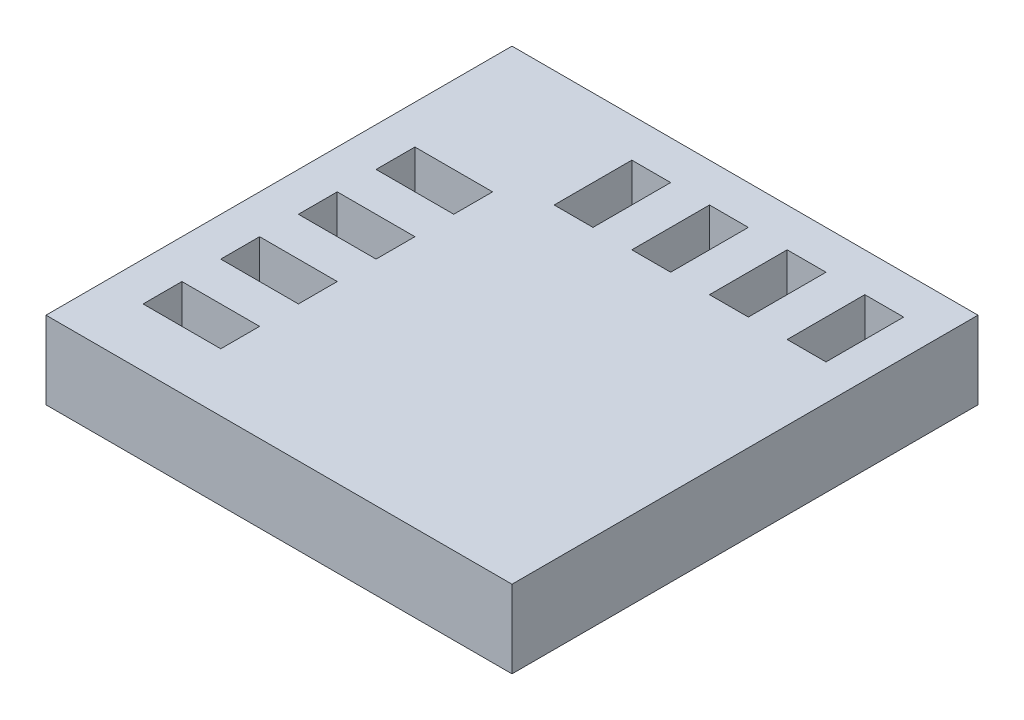
SolidWorks part; units mm, degrees
ref_plane "Front Plane" through (0, 0, 0) normal (0, 0, 1) x (1, 0, 0)
ref_plane "Top Plane" through (0, 0, 0) normal (0, 1, 0) x (1, 0, 0)
ref_plane "Right Plane" through (0, 0, 0) normal (1, 0, 0) x (0, 0, -1)
sketch "Sketch1" plane through (0, 0, 0) normal (0, 1, 0) x (1, 0, 0)
  line L0 (-31.75, -3.175) -> (-19.05, -3.175)
  line L1 (-38.1, -38.1) -> (38.1, -38.1)
  line L2 (-38.1, -38.1) -> (-38.1, 38.1)
  line L3 (-38.1, 38.1) -> (38.1, 38.1)
  line L4 (38.1, -38.1) -> (38.1, 38.1)
  line L5 (-38.1, -38.1) -> (38.1, 38.1) construction
  line L6 (-38.1, 38.1) -> (38.1, -38.1) construction
  line L7 (-31.75, 15.875) -> (-19.05, 15.875)
  line L8 (-31.75, 15.875) -> (-31.75, 9.525)
  line L9 (-31.75, 9.525) -> (-19.05, 9.525)
  line L10 (-19.05, 15.875) -> (-19.05, 9.525)
  line L11 (-31.75, 15.875) -> (-19.05, 9.525) construction
  line L12 (-31.75, 9.525) -> (-19.05, 15.875) construction
  line L13 (-19.05, 3.175) -> (-19.05, -3.175)
  line L14 (-31.75, 3.175) -> (-19.05, 3.175)
  line L15 (-31.75, 3.175) -> (-31.75, -3.175)
  line L16 (-31.75, -15.875) -> (-19.05, -15.875)
  line L17 (-19.05, -9.525) -> (-19.05, -15.875)
  line L18 (-31.75, -9.525) -> (-19.05, -9.525)
  line L19 (-31.75, -9.525) -> (-31.75, -15.875)
  line L20 (-31.75, -28.575) -> (-19.05, -28.575)
  line L21 (-19.05, -22.225) -> (-19.05, -28.575)
  line L22 (-31.75, -22.225) -> (-19.05, -22.225)
  line L23 (-31.75, -22.225) -> (-31.75, -28.575)
  line L24 (0.5443, 31.75) -> (6.8943, 31.75)
  line L25 (-12.1557, 19.05) -> (-5.8057, 19.05)
  line L26 (-12.1557, 19.05) -> (-12.1557, 31.75)
  line L27 (-12.1557, 31.75) -> (-5.8057, 31.75)
  line L28 (-5.8057, 19.05) -> (-5.8057, 31.75)
  line L29 (-12.1557, 19.05) -> (-5.8057, 31.75) construction
  line L30 (-12.1557, 31.75) -> (-5.8057, 19.05) construction
  line L31 (6.8943, 19.05) -> (6.8943, 31.75)
  line L32 (0.5443, 19.05) -> (6.8943, 19.05)
  line L33 (0.5443, 19.05) -> (0.5443, 31.75)
  line L34 (13.2443, 31.75) -> (19.5943, 31.75)
  line L35 (19.5943, 19.05) -> (19.5943, 31.75)
  line L36 (13.2443, 19.05) -> (19.5943, 19.05)
  line L37 (13.2443, 19.05) -> (13.2443, 31.75)
  line L38 (25.9443, 31.75) -> (32.2943, 31.75)
  line L39 (32.2943, 19.05) -> (32.2943, 31.75)
  line L40 (25.9443, 19.05) -> (32.2943, 19.05)
  line L41 (25.9443, 19.05) -> (25.9443, 31.75)
  point P0 (0, 0)
  point P6 (-25.4, 12.7)
  point P11 (-8.9807, 25.4)
  dimension "D1" = 76.2
  dimension "D2" = 76.2
  dimension "D3" = 12.7
  dimension "D4" = 6.35
  dimension "D5" = 12.7
  dimension "D6" = 25.4
  dimension "D8" = 12.7
  dimension "D7" = 4
  dimension "D9" = 4
extrude "Boss-Extrude1" add sketch "Sketch1" along normal blind 12.7
